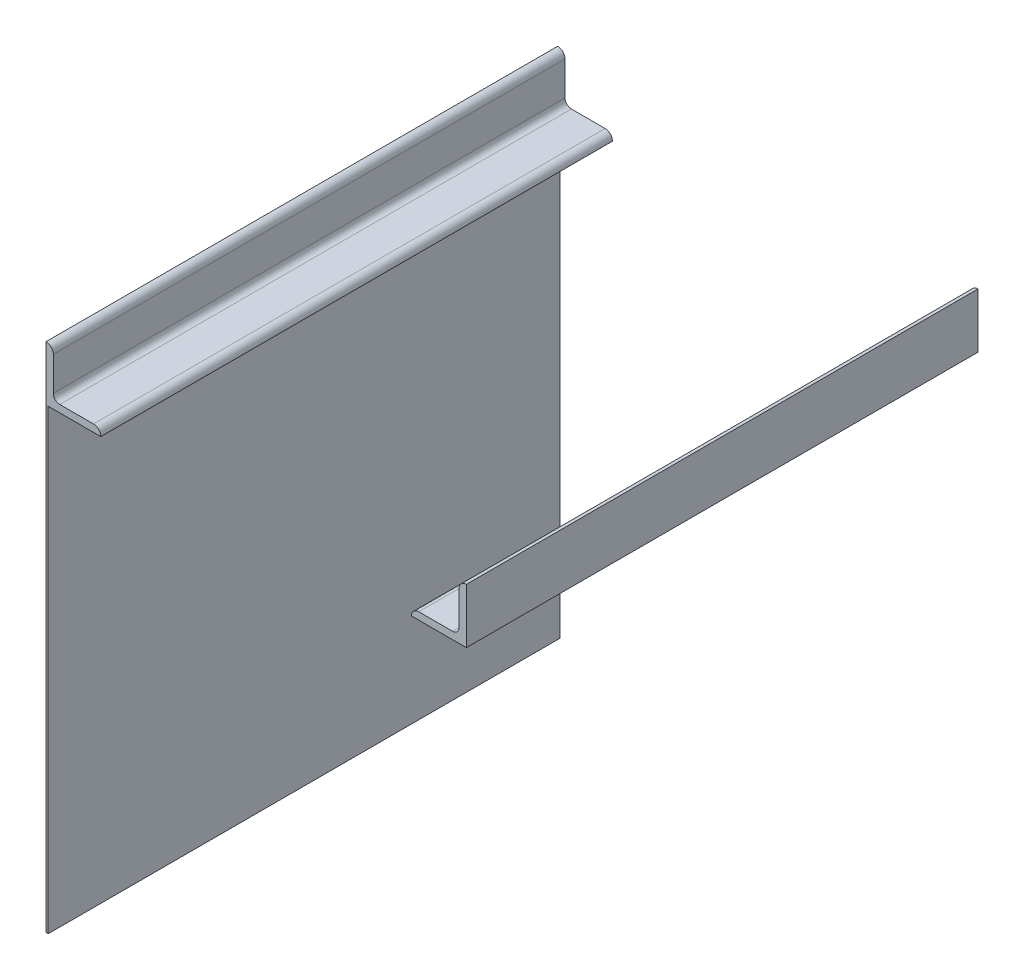
SolidWorks part; units mm, degrees
ref_plane "Front Plane" through (0, 0, 0) normal (0, 0, 1) x (1, 0, 0)
ref_plane "Top Plane" through (0, 0, 0) normal (0, 1, 0) x (1, 0, 0)
ref_plane "Right Plane" through (0, 0, 0) normal (1, 0, 0) x (0, 0, -1)
sketch "Sketch1" plane through (0, 0, 0) normal (0, 1, 0) x (1, 0, 0)
  line L0 (0, 0) -> (0, -280)
  line L1 (230, 0) -> (230, -280)
  dimension "D1" = 280
  dimension "D2" = 230
  dimension "D3" = 280
other "Angle iron 25 X 25 X 4(1)"
ref_plane "Plane1" through (0, 0, 0) normal (0, 0, 1) x (1, 0, 0)
sketch "Sketch11" plane through (0, 0, 0) normal (0, 0, 1) x (1, 0, 0)
  line L0 (0, 0) -> (0, 30)
  line L1 (0, 15) -> (4, 15) construction
  line L2 (4, 26) -> (4, 7.5)
  line L3 (7.5, 4) -> (26, 4)
  line L4 (15, 4) -> (15, 0) construction
  line L5 (30, 0) -> (0, 0)
  arc A0 (30, 0) -> (26, 4) centre (26, 0) ccw
  arc A1 (0, 30) -> (4, 26) centre (0, 26) cw
  arc A2 (7.5, 4) -> (4, 7.5) centre (7.5, 7.5) cw
  point P10 (15, 0)
  point P14 (0, 15)
  point P15 (4, 15)
  point P16 (15, 4)
  point P17 (4, 30)
  point P18 (30, 4)
  point P21 (0, 0)
  dimension "D2" = 4
  dimension "D3" = 30
  dimension "Radius_1" = 3.5
  dimension "D1" = 4
sketch "Sketch12" plane through (0, 0, 0) normal (0, -1, 0) x (1, 0, 0)
  line L0 (0, 280) -> (30, 280) construction
  line L1 (0, 0) -> (1.2, 0)
  line L2 (0, 0) -> (0, 280)
  line L3 (0, 280) -> (1.2, 280)
  line L4 (1.2, 0) -> (1.2, 280)
  dimension "D1" = 1.2
extrude "Boss-Extrude1" add sketch "Sketch12" along normal blind 250 separate body
